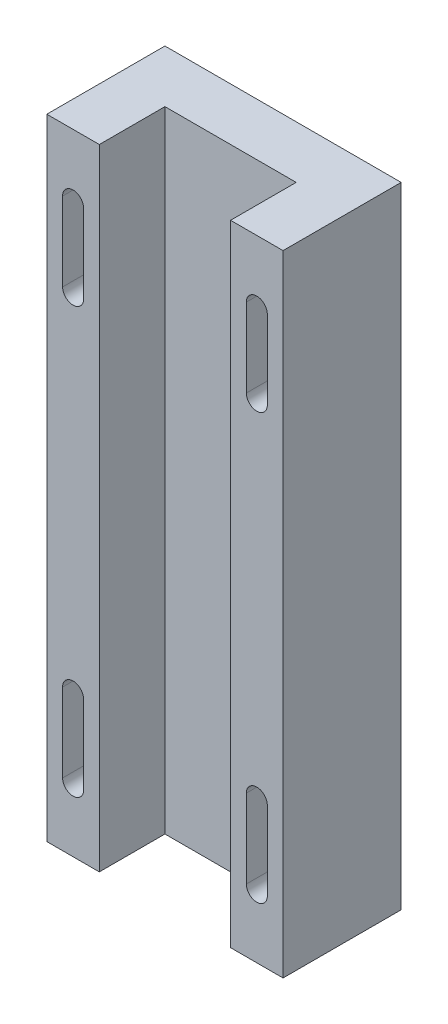
SolidWorks part; units mm, degrees
ref_plane "Front Plane" through (0, 0, 0) normal (0, 0, 1) x (1, 0, 0)
ref_plane "Top Plane" through (0, 0, 0) normal (0, 1, 0) x (1, 0, 0)
ref_plane "Right Plane" through (0, 0, 0) normal (1, 0, 0) x (0, 0, -1)
sketch "Sketch2" plane through (0, 0, 0) normal (0, 1, 0) x (1, 0, 0)
  line L0 (0, 0) -> (-10, 0)
  line L1 (-10, 0) -> (-10, 22.5)
  line L2 (-10, 22.5) -> (35, 22.5)
  line L3 (35, 22.5) -> (35, 0)
  line L4 (35, 0) -> (25, 0)
  line L5 (25, 0) -> (25, 12.5)
  line L6 (25, 12.5) -> (0, 12.5)
  line L7 (0, 12.5) -> (0, 0)
  line L8 (12.5, 12.5) -> (12.5, 22.5) construction
  dimension "D1" = 25
  dimension "D2" = 10
  dimension "D3" = 12.5
extrude "Boss-Extrude1" add sketch "Sketch2" along normal blind 120 contours L1 L2 L3 L4 L5 L6 L7 L0
sketch "Sketch3" plane through (0, 0, 0) normal (0, 0, 1) x (1, 0, 0)
  line L0 (28, 108) -> (28, 93)
  line L1 (35, 120) -> (25, 120) construction
  line L2 (32, 108) -> (32, 93)
  arc A0 (28, 108) -> (32, 108) centre (30, 108) cw
  arc A1 (28, 93) -> (32, 93) centre (30, 93) ccw
  point P6 (30, 110)
  point P9 (30, 120)
  dimension "D2" = 2
  dimension "D1" = 15
  dimension "D3" = 10
extrude "Cut-Extrude1" cut sketch "Sketch3" against normal blind 4 contours L0 A1 L2 A0
ref_plane "Plane1" through (12.5, 0, 0) normal (-1, 0, 0) x (0, 0, -1)
mirror "Mirror1" about plane through (12.5, 0, 0) normal (-1, 0, 0) of "Cut-Extrude1"
ref_plane "Plane2" through (0, 60, 0) normal (0, -1, 0) x (-1, 0, 0)
mirror "Mirror2" about plane through (0, 60, 0) normal (0, -1, 0) of "Mirror1", "Cut-Extrude1"
